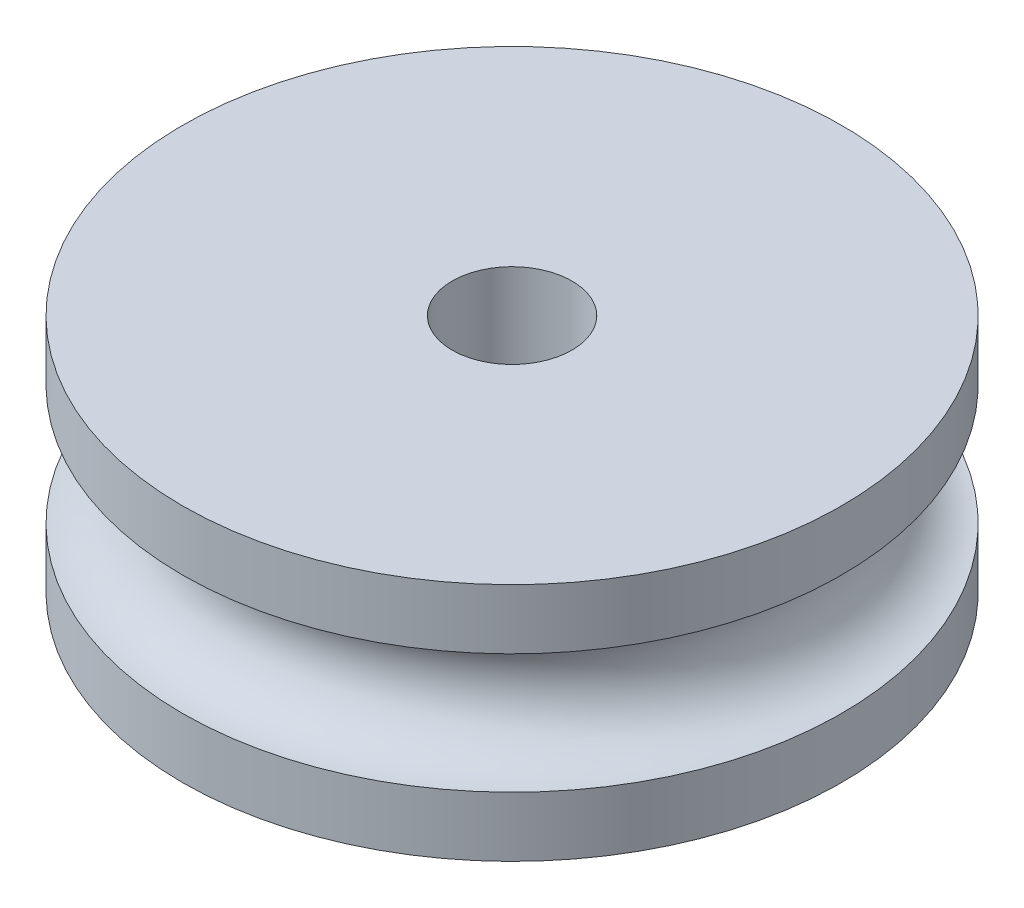
SolidWorks part; units mm, degrees
material "Aleación 1060"
ref_plane "Alzado" through (0, 0, 0) normal (0, 0, 1) x (1, 0, 0)
ref_plane "Planta" through (0, 0, 0) normal (0, 1, 0) x (1, 0, 0)
ref_plane "Vista lateral" through (0, 0, 0) normal (1, 0, 0) x (0, 0, -1)
ref_plane "Plano1" through (0, 0, -44.43) normal (0, 0, -1) x (-1, 0, 0)
sketch "Croquis1" plane through (0, 0, -44.43) normal (0, 0, -1) x (-1, 0, 0)
  line L0 (-81, 54.5264) -> (-81, 53.5264)
  line L1 (-81, 51.5264) -> (-81, 50.5264)
  line L2 (-81, 50.5264) -> (-76.5, 50.5264)
  line L3 (-76.5, 50.5264) -> (-76.5, 54.5264)
  line L4 (-76.5, 54.5264) -> (-81, 54.5264)
  line L5 (-75.5, 50.5264) -> (-75.5, 54.5264) construction
  arc A0 (-81, 53.5264) -> (-81, 51.5264) centre (-81, 52.5264) cw
  point P9 (-81, 54.0264)
  dimension "D1" = 4.5
  dimension "D2" = 5.5
revolve "Revolución1" add sketch "Croquis1" angle 360 about L5
ref_plane "Plano2" through (0, 52.5264, 0) normal (0, 1, 0) x (1, 0, 0)
